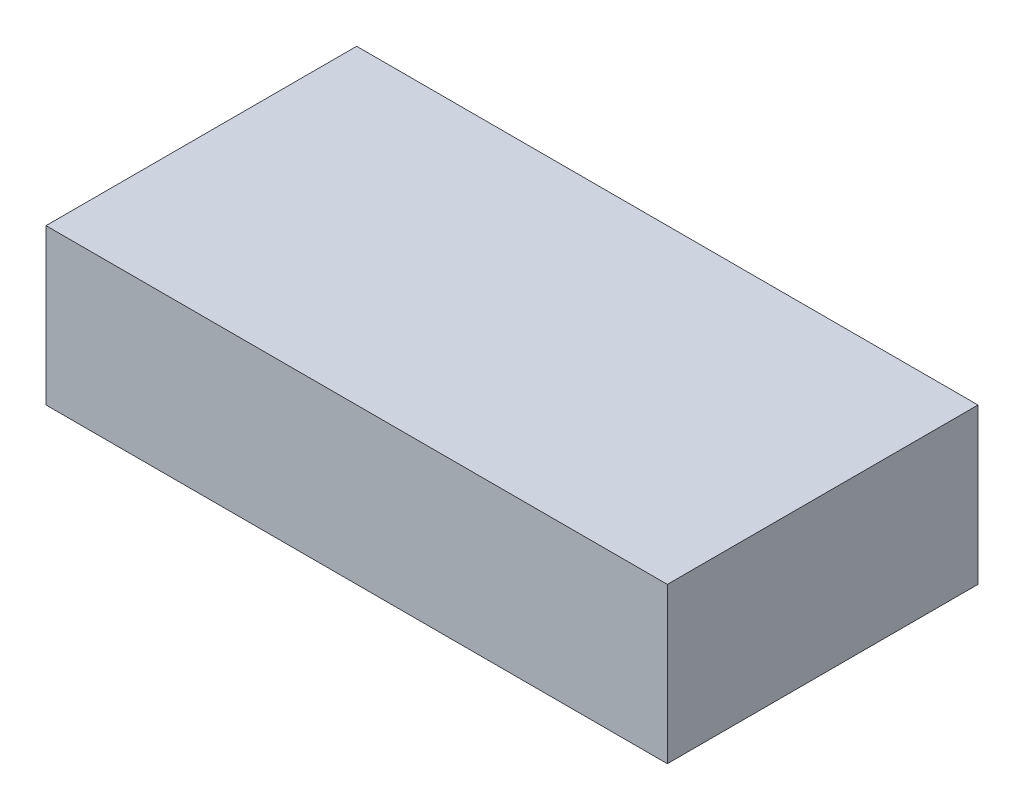
SolidWorks part; units mm, degrees
ref_plane "Alzado" through (0, 0, 0) normal (0, 0, 1) x (1, 0, 0)
ref_plane "Planta" through (0, 0, 0) normal (0, 1, 0) x (1, 0, 0)
ref_plane "Vista lateral" through (0, 0, 0) normal (1, 0, 0) x (0, 0, -1)
sketch "Croquis2" plane through (0, 0, 0) normal (0, 1, 0) x (1, 0, 0)
  line L1 (100, 50) -> (-100, 50)
  line L2 (100, 50) -> (100, -50)
  line L3 (100, -50) -> (-100, -50)
  line L4 (-100, 50) -> (-100, -50)
  line L5 (100, 50) -> (-100, -50) construction
  line L6 (100, -50) -> (-100, 50) construction
  point P0 (0, 0)
  dimension "D1" = 200
  dimension "D2" = 100
extrude "Saliente-Extruir2" add sketch "Croquis2" along normal blind 50
